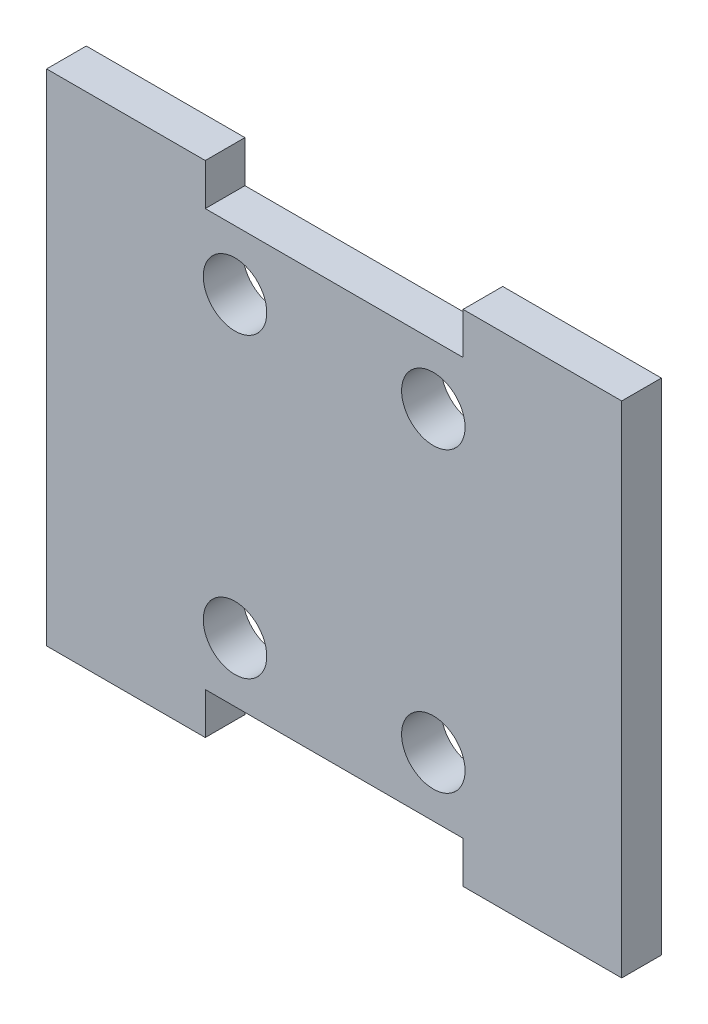
SolidWorks part; units mm, degrees
ref_plane "前视基准面" through (0, 0, 0) normal (0, 0, 1) x (1, 0, 0)
ref_plane "上视基准面" through (0, 0, 0) normal (0, 1, 0) x (1, 0, 0)
ref_plane "右视基准面" through (0, 0, 0) normal (1, 0, 0) x (0, 0, -1)
other "Configuration Table"
sketch "草图1" plane through (0, 0, 0) normal (0, 0, 1) x (1, 0, 0)
  line L0 (-24.5823, -10.5) -> (4.4177, -10.5)
  line L1 (4.4177, -10.5) -> (4.4177, 10.5)
  line L2 (4.4177, 10.5) -> (-24.5823, 10.5)
  line L3 (-24.5823, 10.5) -> (-24.5823, -10.5)
  line L4 (-33.3922, 0) -> (33.3922, 0) construction
  line L5 (-10.0823, 15.5654) -> (-10.0823, -16.292) construction
  line L6 (-24.5823, -12.6) -> (-24.5823, -10.5)
  line L7 (-16.5823, -12.6) -> (-24.5823, -12.6)
  line L8 (-3.5823, -10.5) -> (-3.5823, -12.6)
  line L9 (-10.0823, -15.5654) -> (-10.0823, 16.292) construction
  line L10 (-24.5823, -10.5) -> (-24.5823, -12.6)
  line L11 (-24.5823, -10.5) -> (-24.5823, -12.6)
  line L12 (4.4177, -10.5) -> (4.4177, -12.6)
  line L13 (-3.5823, -12.6) -> (4.4177, -12.6)
  line L14 (4.4177, -12.6) -> (4.4177, -10.5)
  line L15 (-16.5823, -10.5) -> (-16.5823, -12.6)
  line L16 (-16.5823, 10.5) -> (-16.5823, 12.6)
  line L17 (-16.5823, 12.6) -> (-24.5823, 12.6)
  line L18 (-24.5823, 12.6) -> (-24.5823, 10.5)
  line L19 (-3.5823, 12.6) -> (4.4177, 12.6)
  line L20 (-3.5823, 10.5) -> (-3.5823, 12.6)
  line L21 (4.4177, 10.5) -> (4.4177, 12.6)
  circle A0 centre (-5.0823, 7.5) radius 1.6
  circle A1 centre (-15.0823, 7.5) radius 1.6
  circle A2 centre (-15.0823, -7.5) radius 1.6
  circle A3 centre (-5.0823, -7.5) radius 1.6
  point P14 (-10.0823, -12.6)
  point P21 (-10.0823, 12.6)
  dimension "D3" = 3.2
  dimension "D1" = 21
  dimension "D2" = 29
  dimension "D4" = 10
  dimension "D5" = 15
  dimension "D6" = 13
  dimension "D7" = 8
  dimension "D8" = 2.1
extrude "凸台-拉伸1" add sketch "草图1" along normal blind 2 contours L2 L3 L0 L1 A1 A0 A2 A3 | L17 L18 L2 L16 | L2 L21 L19 L20 | L15 L0 L6 L7 | L8 L13 L12 L0
